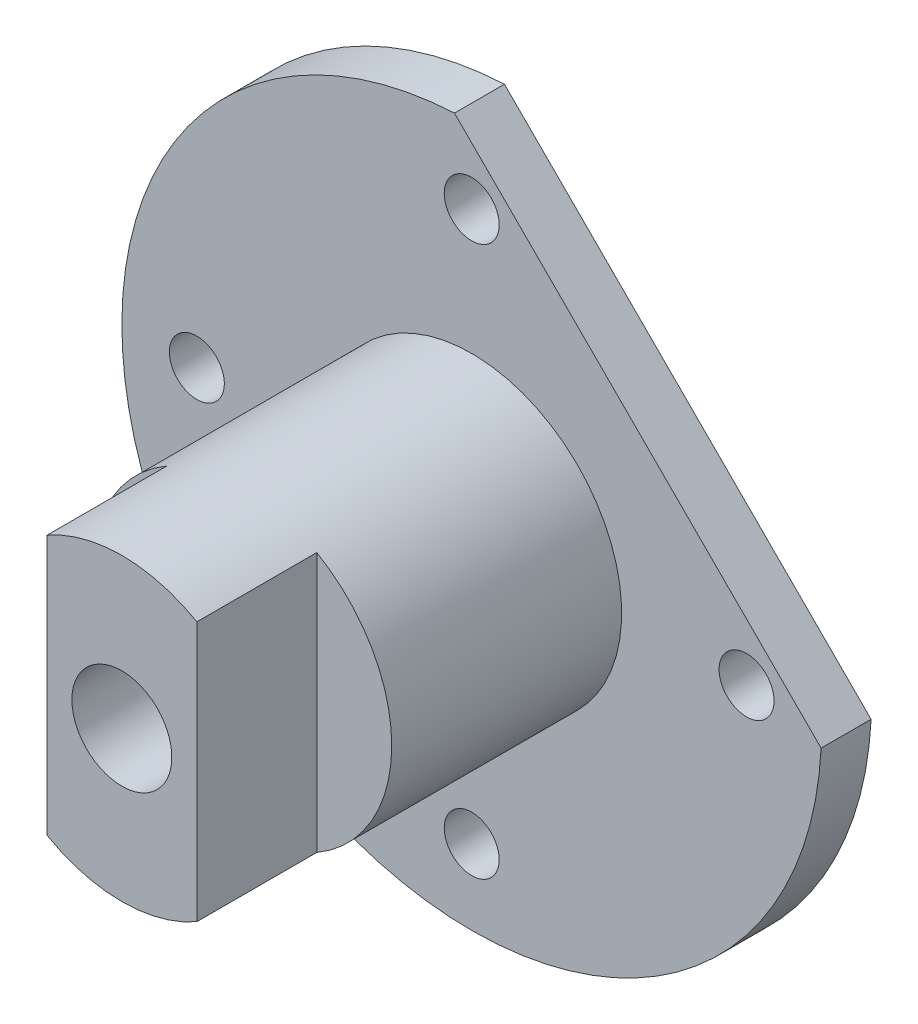
SolidWorks part; units mm, degrees
ref_plane "Front Plane" through (0, 0, 0) normal (0, 0, 1) x (1, 0, 0)
ref_plane "Top Plane" through (0, 0, 0) normal (0, 1, 0) x (1, 0, 0)
ref_plane "Right Plane" through (0, 0, 0) normal (1, 0, 0) x (0, 0, -1)
sketch "Sketch1" plane through (0, 0, 0) normal (0, 0, 1) x (1, 0, 0)
  circle A0 centre (0, 0) radius 15
  dimension "D1" = 30
extrude "Boss-Extrude1" add sketch "Sketch1" along normal blind 40
sketch "Sketch2" plane through (0, 0, 0) normal (0, 0, -1) x (-1, 0, 0)
  circle A0 centre (0, 0) radius 35
  dimension "D1" = 70
extrude "Boss-Extrude2" add sketch "Sketch2" against normal blind 5
sketch "Sketch3" plane through (0, 0, 0) normal (0, 0, -1) x (-1, 0, 0)
  circle A0 centre (0, 0) radius 5
  dimension "D1" = 10
extrude "Cut-Extrude1" cut sketch "Sketch3" against normal through all
sketch "Sketch4" plane through (0, 0, 0) normal (0, 0, -1) x (-1, 0, 0)
  line L1 (8, 0) -> (4, 6.9282)
  line L2 (4, 6.9282) -> (-4, 6.9282)
  line L3 (-4, 6.9282) -> (-8, 0)
  line L4 (-8, 0) -> (-4, -6.9282)
  line L5 (-4, -6.9282) -> (4, -6.9282)
  line L6 (4, -6.9282) -> (8, 0)
  circle A0 centre (0, 0) radius 6.9282 construction
  dimension "D1" = 16
extrude "Cut-Extrude2" cut sketch "Sketch4" against normal blind 10
sketch "Sketch5" plane through (0, 0, 0) normal (0, 1, 0) x (1, 0, 0)
  line L1 (15, -40) -> (7.5, -40)
  line L2 (15, -40) -> (15, -28)
  line L3 (15, -28) -> (7.5, -28)
  line L4 (7.5, -40) -> (7.5, -28)
  dimension "D1" = 7.5
  dimension "D2" = 12
extrude "Cut-Extrude3" cut sketch "Sketch5" against normal through all and the other way through all
mirror "Mirror1" about plane through (0, 0, 0) normal (1, 0, 0) of "Cut-Extrude3"
hole_wizard "M5 Clearance Hole1" positions "Sketch7" profile "Sketch6" hole size "M5" standard "ANSI Metric" end condition through all
sketch "Sketch7" plane through (0, 0, 0) normal (0, 0, -1) x (-1, 0, 0)
  circle A0 centre (0, 0) radius 27.5 construction
  point P0 (0, 27.5)
  point P13 (-27.5, 0)
  point P15 (27.5, 0)
  point P17 (0, -27.5)
  dimension "D1" = 55
sketch "Sketch6" plane through (0, 27.5, 0) normal (1, 0, 0) x (0, 1, 0)
  line L0 (0, 0) -> (0, 40)
  line L1 (0, 40) -> (2.75, 40)
  line L2 (2.75, 40) -> (2.75, 0)
  line L5 (2.75, 0) -> (0, 0)
  line L11 (0, -6.35) -> (0, 107.95) construction
  dimension "Thru Hole Dia." = 5.5
  dimension "Thru Hole Depth" = 40
sketch "Sketch8" plane through (0, 0, 0) normal (0, 0, -1) x (-1, 0, 0)
  line L0 (-34.9575, -1.7235) -> (1.7235, 34.9575)
  line L1 (0, 0) -> (-16.617, 16.617) construction
  line L2 (0, 0) -> (0, 35) construction
  circle A0 centre (0, 0) radius 35 construction
  arc A1 (1.7235, 34.9575) -> (-34.9575, -1.7235) centre (0, 0) ccw
  dimension "D1" = 45
  dimension "D2" = 23.5
extrude "Cut-Extrude4" cut sketch "Sketch8" against normal through all
